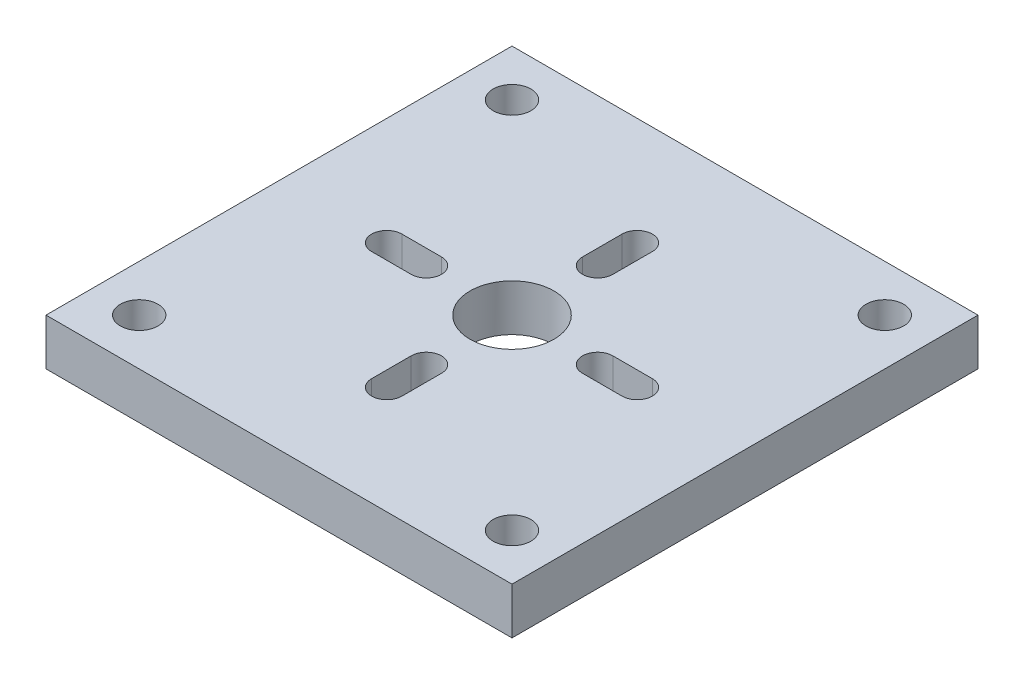
SolidWorks part; units mm, degrees
ref_plane "Front Plane" through (0, 0, 0) normal (0, 0, 1) x (1, 0, 0)
ref_plane "Top Plane" through (0, 0, 0) normal (0, 1, 0) x (1, 0, 0)
ref_plane "Right Plane" through (0, 0, 0) normal (1, 0, 0) x (0, 0, -1)
sketch "Sketch1" plane through (0, 0, 0) normal (0, 1, 0) x (1, 0, 0)
  line L1 (50, 50) -> (-50, 50)
  line L2 (50, 50) -> (50, -50)
  line L3 (50, -50) -> (-50, -50)
  line L4 (-50, 50) -> (-50, -50)
  line L5 (50, 50) -> (-50, -50) construction
  line L6 (50, -50) -> (-50, 50) construction
  point P0 (0, 0)
  dimension "D1" = 100
  dimension "D2" = 100
extrude "base" add sketch "Sketch1" along normal blind 10 contours L1 L4 L3 L2
sketch "Sketch2" plane through (0, 10, 0) normal (0, 1, 0) x (1, 0, 0)
  circle A0 centre (0, 0) radius 9
  dimension "D1" = 18
extrude "actuator cut" cut sketch "Sketch2" against normal blind 40
sketch "Sketch3" plane through (0, 10, 0) normal (0, 1, 0) x (1, 0, 0)
  line L0 (0, -26.8701) -> (0, -18.3848) construction
  line L1 (0, 0) -> (0, 19) construction
  line L2 (3.25, -26.8701) -> (3.25, -18.3848)
  line L8 (0, 0) -> (19, 0) construction
  line L12 (-3.25, -26.8701) -> (-3.25, -18.3848)
  line L17 (26.8701, 0) -> (18.3848, 0) construction
  line L18 (26.8701, 3.25) -> (18.3848, 3.25)
  line L19 (26.8701, -3.25) -> (18.3848, -3.25)
  line L20 (-26.8701, 0) -> (-18.3848, 0) construction
  line L21 (-26.8701, -3.25) -> (-18.3848, -3.25)
  line L22 (-26.8701, 3.25) -> (-18.3848, 3.25)
  line L23 (0, 26.8701) -> (0, 18.3848) construction
  line L24 (-3.25, 26.8701) -> (-3.25, 18.3848)
  line L25 (3.25, 26.8701) -> (3.25, 18.3848)
  arc A16 (26.8701, 3.25) -> (26.8701, -3.25) centre (26.8701, 0) cw
  arc A17 (18.3848, -3.25) -> (18.3848, 3.25) centre (18.3848, 0) cw
  arc A18 (3.25, -26.8701) -> (-3.25, -26.8701) centre (0, -26.8701) cw
  arc A19 (-3.25, -18.3848) -> (3.25, -18.3848) centre (0, -18.3848) cw
  arc A20 (-26.8701, -3.25) -> (-26.8701, 3.25) centre (-26.8701, 0) cw
  arc A21 (-18.3848, 3.25) -> (-18.3848, -3.25) centre (-18.3848, 0) cw
  arc A22 (-3.25, 26.8701) -> (3.25, 26.8701) centre (0, 26.8701) cw
  arc A23 (3.25, 18.3848) -> (-3.25, 18.3848) centre (0, 18.3848) cw
  point P0 (0, 0)
  point P5 (0, -22.6274)
  point P15 (-22.6274, 0)
  point P23 (0, 22.6274)
  point P30 (22.6274, 0)
  point P35 (0, 0)
  dimension "D1" = 26.8701
  dimension "D3" = 3.25
  dimension "D2" = 18.3848
  dimension "D4" = 4
  dimension "D7" = 0
extrude "Cut-Extrude1" cut sketch "Sketch3" against normal up to next
sketch "Sketch4" [suppressed] plane through (0, 0, 0) normal (0, -1, 0) x (1, 0, 0)
  line L0 (2.373, 19) -> (2.373, 13) construction
  line L1 (-4.127, 13) -> (-4.127, 19) construction
  line L2 (13, 6.377) -> (19, 6.377)
  line L3 (19, -5.123) -> (13, -5.123)
  line L4 (6.377, -13.25) -> (6.377, -19.25)
  line L5 (-5.123, -19.25) -> (-5.123, -13.25)
  line L6 (-13.25, -6.627) -> (-19.25, -6.627)
  line L7 (-19.25, 4.873) -> (-13.25, 4.873)
  line L8 (2.373, 19) -> (2.373, 13) construction
  line L9 (-4.127, 13) -> (-4.127, 19) construction
  line L16 (4.873, 19) -> (4.873, 13)
  line L17 (-6.627, 13) -> (-6.627, 19)
  arc A0 (-4.127, 13) -> (2.373, 13) centre (-0.877, 13) ccw construction
  arc A1 (2.373, 19) -> (-4.127, 19) centre (-0.877, 19) ccw construction
  arc A2 (13, 6.377) -> (13, -5.123) centre (13, 0.627) ccw
  arc A3 (19, -5.123) -> (19, 6.377) centre (19, 0.627) ccw
  arc A4 (6.377, -13.25) -> (-5.123, -13.25) centre (0.627, -13.25) ccw
  arc A5 (-5.123, -19.25) -> (6.377, -19.25) centre (0.627, -19.25) ccw
  arc A6 (-13.25, -6.627) -> (-13.25, 4.873) centre (-13.25, -0.877) ccw
  arc A7 (-19.25, 4.873) -> (-19.25, -6.627) centre (-19.25, -0.877) ccw
  arc A8 (-4.127, 13) -> (2.373, 13) centre (-0.877, 13) ccw construction
  arc A9 (2.373, 19) -> (-4.127, 19) centre (-0.877, 19) ccw construction
  arc A16 (-6.627, 13) -> (4.873, 13) centre (-0.877, 13) ccw
  arc A17 (4.873, 19) -> (-6.627, 19) centre (-0.877, 19) ccw
  point P33 (-0.125, -0.125)
  dimension "D1" = 2.5
  dimension "D2" = 4
split line "Split Line1" [suppressed]
sketch "Sketch5" plane through (0, 10, 0) normal (0, 1, 0) x (1, 0, 0)
  line L0 (-40, 40) -> (-40, -40) construction
  line L1 (-40, -40) -> (40, -40) construction
  circle A0 centre (-40, -40) radius 4.05
  circle A1 centre (-40, 40) radius 4.05
  circle A2 centre (40, -40) radius 4.05
  circle A3 centre (40, 40) radius 4.05
  point P8 (-40, 0)
  point P9 (0, -40)
  dimension "D3" = 8.1
  dimension "D1" = 80
  dimension "D2" = 80
extrude "Cut-Extrude2" cut sketch "Sketch5" against normal up to next
sketch "Sketch6" [suppressed] plane through (0, 0, 0) normal (0, -1, 0) x (1, 0, 0)
  circle A0 centre (-40, 40) radius 4
  circle A1 centre (40, 40) radius 4
  circle A2 centre (40, -40) radius 4
  circle A3 centre (-40, -40) radius 4
  dimension "D1" = 8
extrude "Cut-Extrude3" [suppressed] cut sketch "Sketch6" against normal through all
